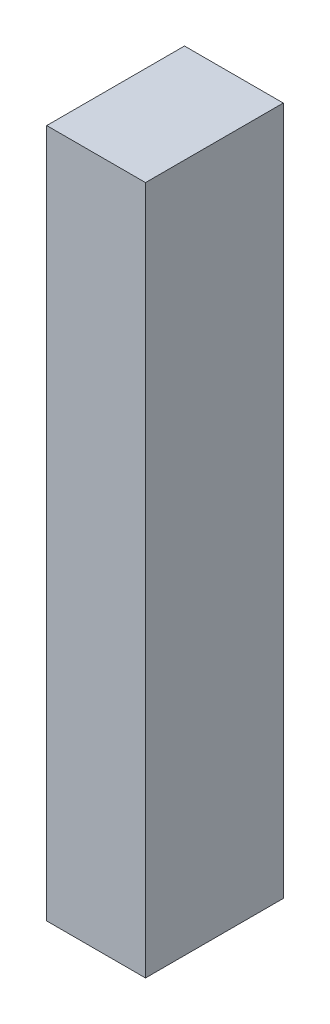
SolidWorks part; units mm, degrees
material "6061 Alloy"
ref_plane "Front Plane" through (0, 0, 0) normal (0, 0, 1) x (1, 0, 0)
ref_plane "Top Plane" through (0, 0, 0) normal (0, 1, 0) x (1, 0, 0)
ref_plane "Right Plane" through (0, 0, 0) normal (1, 0, 0) x (0, 0, -1)
sketch "Sketch2" plane through (0, 0, 0) normal (0, 1, 0) x (1, 0, 0)
  line L1 (0, 0) -> (71.7, 0)
  line L2 (0, 0) -> (0, -100)
  line L3 (0, -100) -> (71.7, -100)
  line L4 (71.7, 0) -> (71.7, -100)
  dimension "D1" = 71.7
  dimension "D2" = 100
extrude "Boss-Extrude1" add sketch "Sketch2" along normal blind 500
